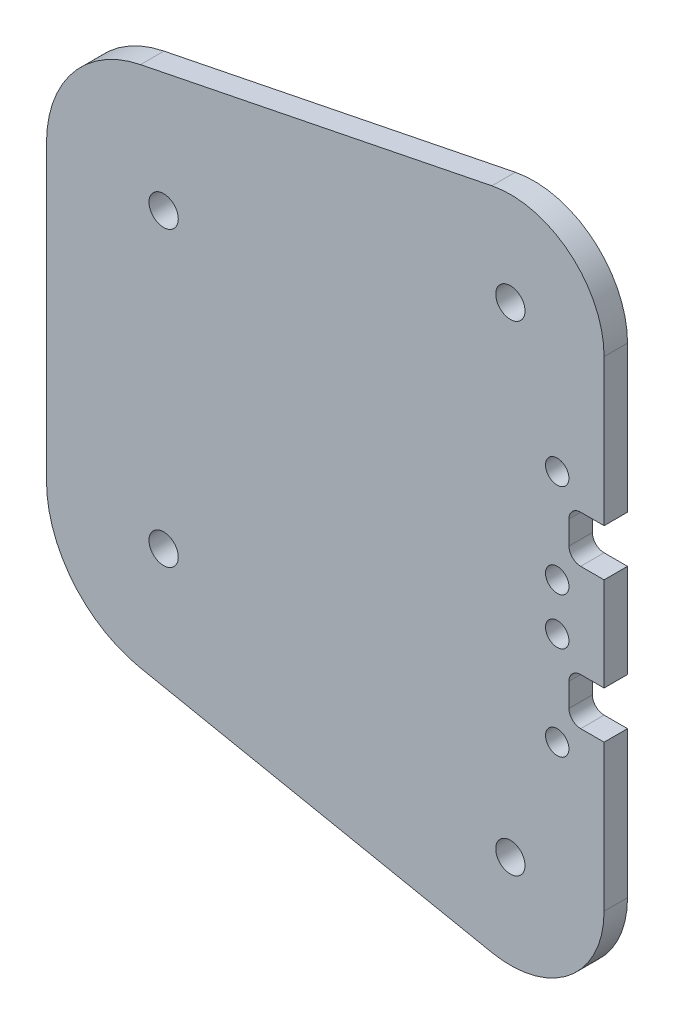
SolidWorks part; units mm, degrees
material "自訂玻璃纖維"
ref_plane "前基準面" through (0, 0, 0) normal (0, 0, 1) x (1, 0, 0)
ref_plane "上基準面" through (0, 0, 0) normal (0, 1, 0) x (1, 0, 0)
ref_plane "右基準面" through (0, 0, 0) normal (1, 0, 0) x (0, 0, -1)
sketch "草圖1" plane through (0, 0, 0) normal (0, 0, 1) x (1, 0, 0)
  line L0 (-28.5419, -9.118) -> (-28.5419, -34.118)
  line L1 (-20.5158, 0.6853) -> (9.479, 6.7246)
  line L2 (16.0581, -14.618) -> (16.0581, -16.618)
  line L4 (19.0581, -13.618) -> (17.0581, -13.618)
  line L5 (19.0581, -29.618) -> (17.0581, -29.618)
  line L6 (19.0581, -17.618) -> (17.0581, -17.618)
  line L7 (19.0581, -17.618) -> (19.0581, -25.618)
  line L8 (19.0581, -25.618) -> (17.0581, -25.618)
  line L9 (-20.5158, -43.9213) -> (9.479, -49.9606)
  line L10 (16.0581, -26.618) -> (16.0581, -28.618)
  line L11 (19.0581, -29.618) -> (19.0581, -42.118)
  line L12 (19.0581, -13.618) -> (19.0581, -1.118)
  circle A0 centre (-18.5419, -9.118) radius 1.25
  arc A1 (17.0581, -13.618) -> (16.0581, -14.618) centre (17.0581, -14.618) ccw
  arc A2 (16.0581, -16.618) -> (17.0581, -17.618) centre (17.0581, -16.618) ccw
  circle A6 centre (15.0581, -11.618) radius 1
  circle A7 centre (15.0581, -19.618) radius 1
  circle A8 centre (15.0581, -23.618) radius 1
  circle A9 centre (-18.5419, -34.118) radius 1.25
  arc A10 (19.0581, -42.118) -> (9.479, -49.9606) centre (11.0581, -42.118) cw
  circle A12 centre (11.0581, -1.118) radius 1.25
  arc A13 (-28.5419, -9.118) -> (-20.5158, 0.6853) centre (-18.5419, -9.118) cw
  arc A14 (19.0581, -1.118) -> (9.479, 6.7246) centre (11.0581, -1.118) ccw
  circle A15 centre (15.0581, -31.618) radius 1
  arc A16 (16.0581, -28.618) -> (17.0581, -29.618) centre (17.0581, -28.618) ccw
  arc A17 (17.0581, -25.618) -> (16.0581, -26.618) centre (17.0581, -26.618) ccw
  circle A18 centre (11.0581, -42.118) radius 1.25
  arc A20 (-28.5419, -34.118) -> (-20.5158, -43.9213) centre (-18.5419, -34.118) ccw
  point P3 (11.0581, -1.118)
  point P9 (-18.5419, -34.118)
  point P10 (19.0581, -42.118)
  point P12 (-18.5419, -9.118)
  point P13 (19.0581, -1.118)
  point P14 (-18.5419, -34.118)
  point P23 (-18.5419, -34.118)
  point P24 (-18.5419, -9.118)
  point P25 (-8.5419, -9.118)
  dimension "D4" = 8
  dimension "D5" = 8
  dimension "D6" = 2
  dimension "D11" = 4
  dimension "D12" = 2
  dimension "D13" = 2
extrude "填料-伸長2" add sketch "草圖1" along normal blind 2
